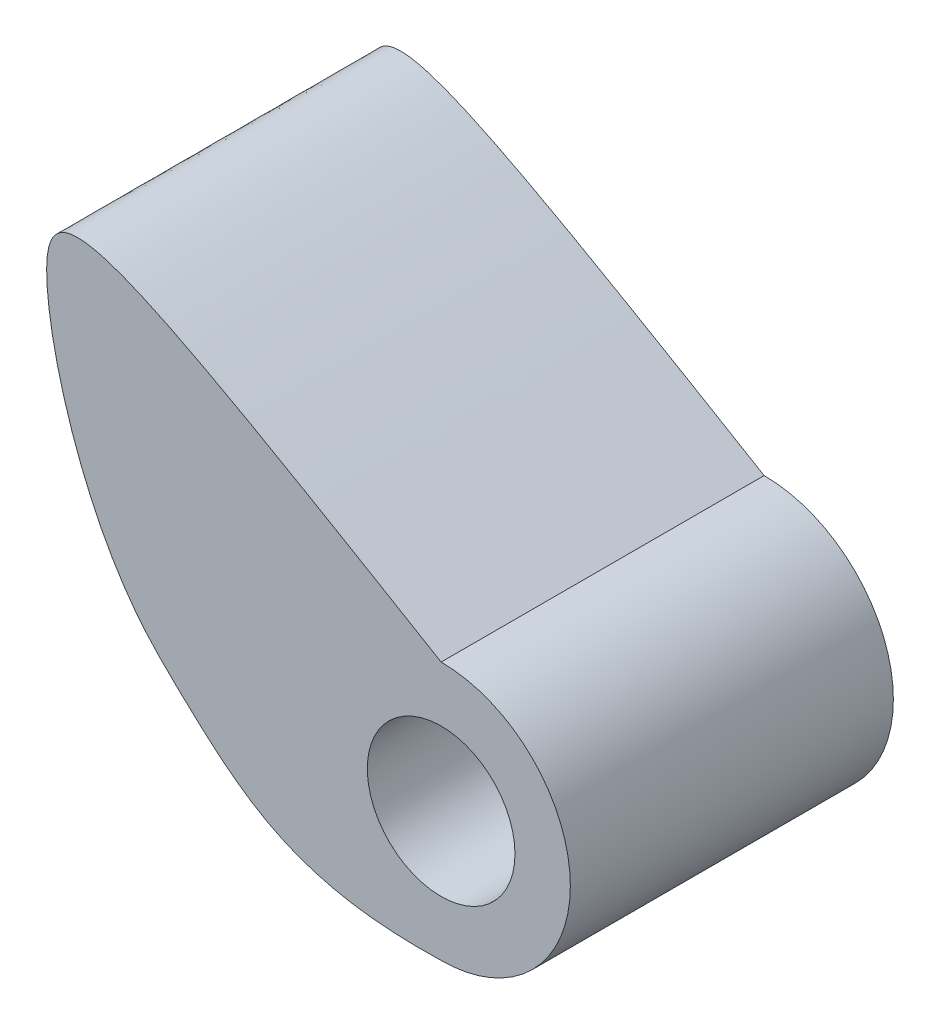
SolidWorks part; units mm, degrees
ref_plane "Plan de face" through (0, 0, 0) normal (0, 0, 1) x (1, 0, 0)
ref_plane "Plan de dessus" through (0, 0, 0) normal (0, 1, 0) x (1, 0, 0)
ref_plane "Plan de droite" through (0, 0, 0) normal (1, 0, 0) x (0, 0, -1)
sketch "Esquisse1" plane through (0, 0, 0) normal (0, 0, 1) x (1, 0, 0)
  line L0 (-20.7103, 16.7759) -> (0, 0) construction
  circle A0 centre (0, 0) radius 4
  circle A1 centre (0, 0) radius 7
  spline S0 degree 3 poles (0, -7) (-7.6745, -7.2244) (-11.1284, -4.4104) (-19.0739, 3.2533) (-23.9314, 20.6602) (-17.9595, 17.6486) (0, 7) knots 0 0 0 0 0.270182 0.329199 0.590176 1 1 1 1
  dimension "D1" = 8
  dimension "D2" = 14
extrude "Boss.-Extru.1" add sketch "Esquisse1" against normal blind 17.5
